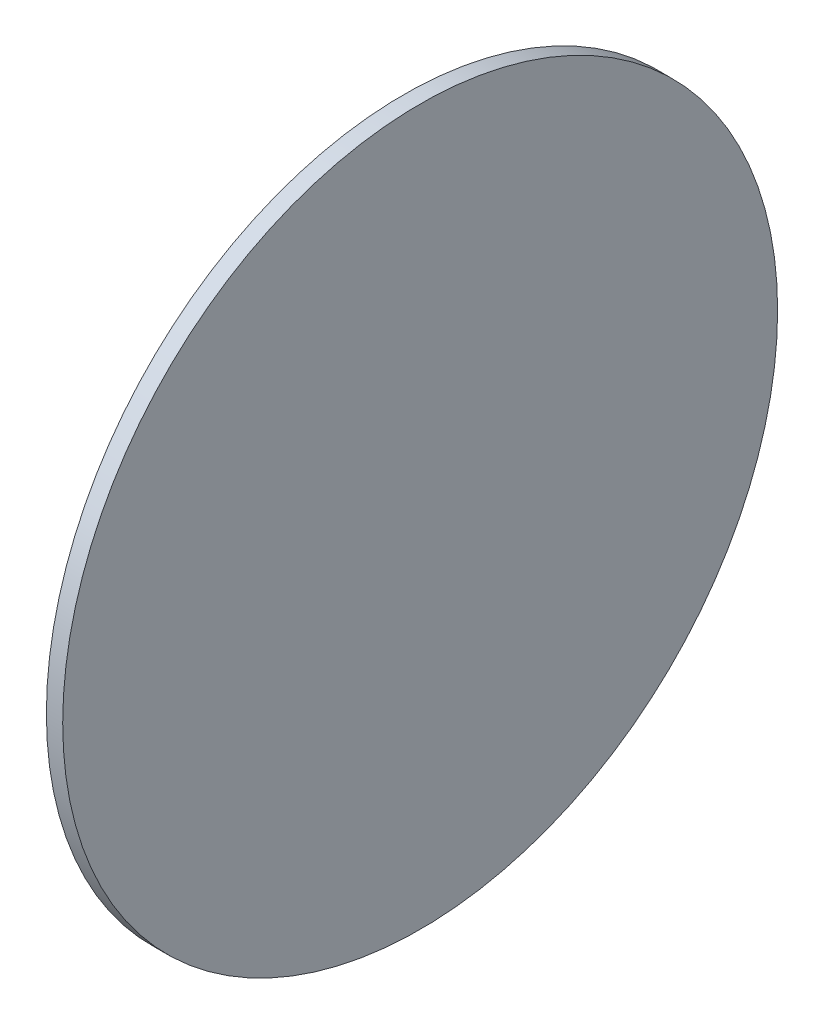
SolidWorks part; units mm, degrees
ref_plane "Front Plane" through (0, 0, 0) normal (0, 0, 1) x (1, 0, 0)
ref_plane "Top Plane" through (0, 0, 0) normal (0, 1, 0) x (1, 0, 0)
ref_plane "Right Plane" through (0, 0, 0) normal (1, 0, 0) x (0, 0, -1)
sketch "S_cyl1" plane through (0, 0, 0) normal (1, 0, 0) x (0, 0, -1)
  circle A0 centre (0, 0) radius 25.2
  dimension "D1_S_cyl1" = 50.4
extrude "Boss_1" add sketch "S_cyl1" along normal blind 1.15
equation "\"plate_t\" = 3"
equation "\"clearance\" = 0.5"
